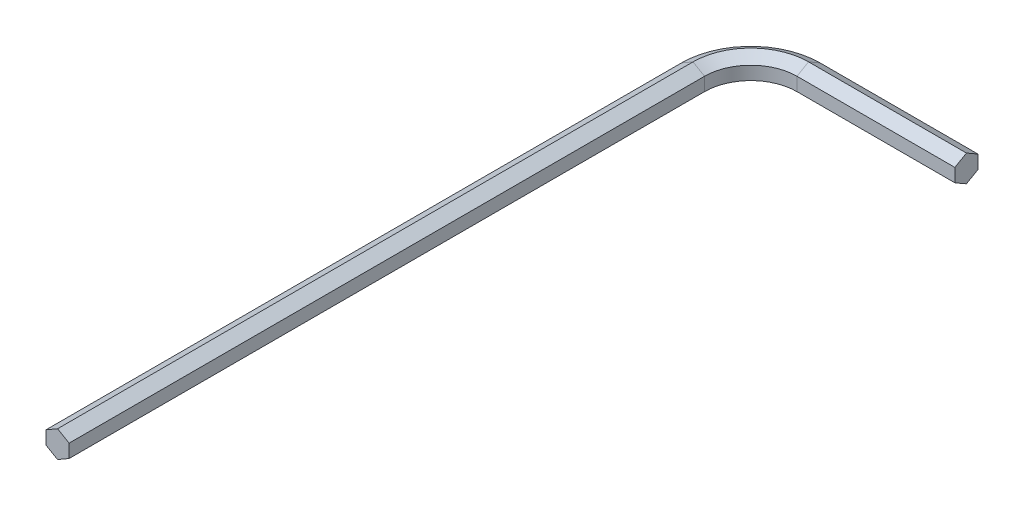
SolidWorks part; units mm, degrees
ref_plane "Front Plane" through (0, 0, 0) normal (0, 0, 1) x (1, 0, 0)
ref_plane "Top Plane" through (0, 0, 0) normal (0, 1, 0) x (1, 0, 0)
ref_plane "Right Plane" through (0, 0, 0) normal (1, 0, 0) x (0, 0, -1)
sketch "Sketch1" plane through (0, 0, 0) normal (0, 1, 0) x (1, 0, 0)
  line L0 (0, 0) -> (0, 41.25)
  line L1 (3.75, 45) -> (14, 45)
  arc A0 (0, 41.25) -> (3.75, 45) centre (3.75, 41.25) cw
  point P6 (0, 45)
  dimension "D3" = 3.75
  dimension "D1" = 14
  dimension "D2" = 45
sketch "Sketch2" plane through (0, 0, 0) normal (0, 0, 1) x (1, 0, 0)
  line L1 (0, -0.866) -> (0.75, -0.433)
  line L2 (0.75, -0.433) -> (0.75, 0.433)
  line L3 (0.75, 0.433) -> (0, 0.866)
  line L4 (0, 0.866) -> (-0.75, 0.433)
  line L5 (-0.75, 0.433) -> (-0.75, -0.433)
  line L6 (-0.75, -0.433) -> (0, -0.866)
  circle A0 centre (0, 0) radius 0.75 construction
  point P1 (0, 0.75)
  point P10 (0, 0)
  dimension "D1" = 1.5
sweep "Sweep1" add profiles "Sketch2" path "Sketch1"
